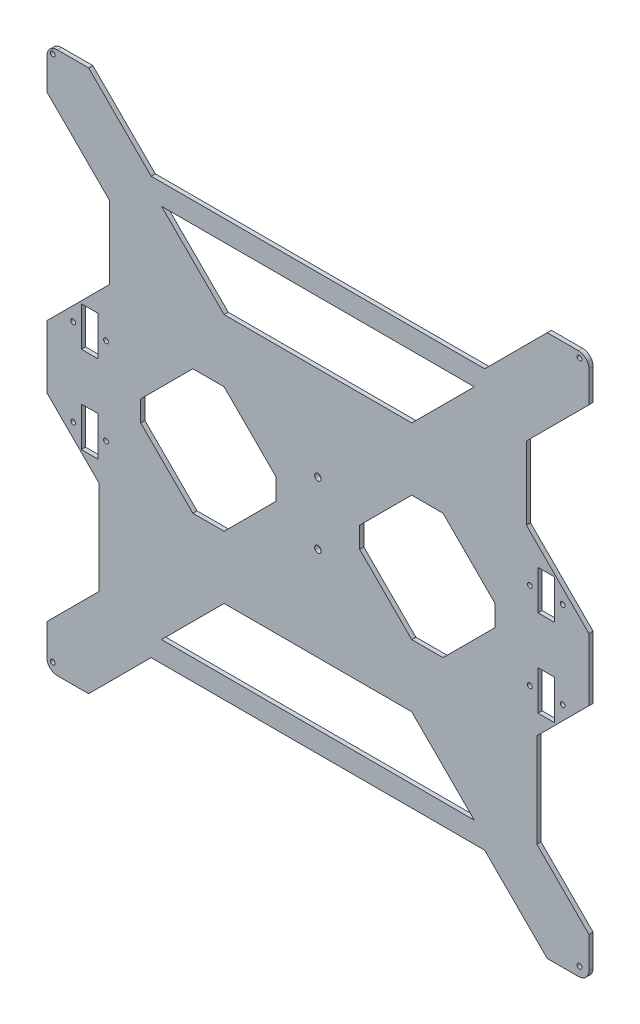
SolidWorks part; units mm, degrees
ref_plane "Front Plane" through (0, 0, 0) normal (0, 0, 1) x (1, 0, 0)
ref_plane "Top Plane" through (0, 0, 0) normal (0, 1, 0) x (1, 0, 0)
ref_plane "Right Plane" through (0, 0, 0) normal (1, 0, 0) x (0, 0, -1)
sketch "Model" plane through (0, 0, 0) normal (0, 0, 1) x (1, 0, 0)
  line L0 (38.5361, 132.6139) -> (38.5361, 132.4727)
  line L1 (38.5361, -178.6774) -> (38.5361, -178.7219)
  line L2 (-253.5639, -197.5861) -> (-253.5639, -197.7273)
  line L3 (-252.5813, 70.3317) -> (-252.5813, 25.8817)
  line L4 (-258.9313, -82.0683) -> (-258.9313, -139.2183)
  line L5 (38.5361, 132.6139) -> (38.5361, 132.4727)
  line L6 (38.5361, -178.6774) -> (38.5361, -178.7219)
  line L7 (7.7687, -139.2183) -> (7.7687, -82.0683)
  line L8 (1.4187, 25.8817) -> (1.4187, 70.3317)
  line L9 (-23.9813, 95.7317) -> (-227.1813, 95.7317)
  line L10 (-290.6813, 108.4317) -> (-252.5813, 70.3317)
  line L11 (-30.3313, -145.5683) -> (-68.4313, -107.4683)
  line L12 (-23.9813, -158.2683) -> (14.1187, -196.3683)
  line L13 (39.5187, 108.4317) -> (39.5187, 127.4817)
  line L14 (-227.1813, 95.7317) -> (-265.2813, 133.8317)
  line L15 (-220.8313, 83.0317) -> (-182.7313, 44.9317)
  line L16 (-274.6813, -57.7288) -> (-254.6813, -57.7288) construction
  line L17 (39.5187, -170.9683) -> (7.7687, -139.2183)
  line L18 (-265.2813, -196.3683) -> (-227.1813, -158.2683)
  line L19 (-182.7313, -107.4683) -> (-68.4313, -107.4683)
  line L20 (-264.6813, -57.7288) -> (-264.6813, -43.5832) construction
  line L21 (1.4187, 70.3317) -> (39.5187, 108.4317)
  line L22 (-23.9813, 95.7317) -> (14.1187, 133.8317)
  line L23 (-30.3313, 83.0317) -> (-68.4313, 44.9317)
  line L25 (-258.9313, -139.2183) -> (-290.6813, -170.9683)
  line L26 (-182.7313, 44.9317) -> (-68.4313, 44.9317)
  line L27 (-220.8313, -145.5683) -> (-182.7313, -107.4683)
  line L28 (-220.8313, -145.5683) -> (-30.3313, -145.5683)
  line L29 (-258.9313, -82.0683) -> (-290.6813, -50.3183)
  line L30 (-290.6813, -12.2183) -> (-290.6813, -50.3183)
  line L31 (-274.6813, -56.2683) -> (-274.6813, -31.2683) construction
  line L32 (-290.6813, -12.2183) -> (-252.5813, 25.8817)
  line L33 (-201.7813, -69.3683) -> (-233.5313, -37.6183)
  line L34 (-182.7313, -69.3683) -> (-201.7813, -69.3683)
  line L35 (1.4187, 25.8817) -> (39.5187, -12.2183)
  line L36 (39.5187, -12.2183) -> (39.5187, -50.3183)
  line L37 (-150.9813, -37.6183) -> (-182.7313, -69.3683)
  line L38 (39.5187, -50.3183) -> (22.4579, -67.3791)
  line L39 (22.4579, -67.3791) -> (7.7687, -82.0683)
  line L40 (-100.1813, -37.6183) -> (-100.1813, -24.9183)
  line L41 (-150.9813, -37.6183) -> (-150.9813, -24.9183)
  line L42 (-150.9813, -24.9183) -> (-182.7313, 6.8317)
  line L43 (-182.7313, 6.8317) -> (-201.7813, 6.8317)
  line L44 (-201.7813, 6.8317) -> (-233.5313, -24.9183)
  line L45 (-233.5313, -24.9183) -> (-233.5313, -37.6183)
  line L46 (-17.6313, -24.9183) -> (-17.6313, -37.6183)
  line L47 (-49.3813, 6.8317) -> (-17.6313, -24.9183)
  line L48 (-220.8313, 83.0317) -> (-30.3313, 83.0317)
  line L49 (-68.4313, 6.8317) -> (-49.3813, 6.8317)
  line L50 (-100.1813, -24.9183) -> (-68.4313, 6.8317)
  line L51 (-100.1813, -37.6183) -> (-68.4313, -69.3683)
  line L52 (-68.4313, -69.3683) -> (-49.3813, -69.3683)
  line L53 (-49.3813, -69.3683) -> (-17.6313, -37.6183)
  line L58 (-265.2813, -196.3683) -> (-284.3313, -196.3683)
  line L59 (-290.6813, -190.0183) -> (-290.6813, -170.9683)
  line L60 (-290.6813, 108.4317) -> (-290.6813, 127.4817)
  line L61 (-284.3313, 133.8317) -> (-265.2813, 133.8317)
  line L62 (14.1187, 133.8317) -> (33.1687, 133.8317)
  line L64 (39.5187, -170.9683) -> (39.5187, -190.0183)
  line L65 (33.1687, -196.3683) -> (14.1187, -196.3683)
  line L71 (-227.1813, -158.2683) -> (-23.9813, -158.2683)
  line L72 (38.5361, -178.6774) -> (38.5361, -178.7219)
  line L74 (-227.1813, -158.2683) -> (-23.9813, -158.2683)
  line L75 (38.5361, -178.6774) -> (38.5361, -178.7219)
  line L77 (-125.5813, 95.7317) -> (-125.5813, -158.2683) construction
  line L78 (-290.6813, -31.2683) -> (39.5187, -31.2683) construction
  arc A0 (33.1687, -196.3683) -> (39.5187, -190.0183) centre (33.1687, -190.0183) ccw
  arc A1 (-290.6813, -190.0183) -> (-284.3313, -196.3683) centre (-284.3313, -190.0183) ccw
  arc A2 (-290.6813, 127.4817) -> (-284.3313, 133.8317) centre (-284.3313, 127.4817) cw
  arc A3 (33.1687, 133.8317) -> (39.5187, 127.4817) centre (33.1687, 127.4817) cw
  circle A4 centre (-287.1253, -190.6025) radius 1.4605
  circle A5 centre (33.7529, -190.6025) radius 1.4605
  circle A6 centre (33.7529, 130.2757) radius 1.4605
  circle A7 centre (-287.1253, 130.2757) radius 1.4605
  circle A8 centre (-274.6813, -57.7288) radius 1.4605
  circle A9 centre (-254.6813, -57.7288) radius 1.4605
  circle A10 centre (23.5187, -57.7288) radius 1.4605
  circle A11 centre (3.5187, -57.7288) radius 1.4605
  circle A12 centre (23.5187, -4.8078) radius 1.4605
  circle A13 centre (3.5187, -4.8078) radius 1.4605
  circle A14 centre (-254.6813, -4.8078) radius 1.4605
  circle A15 centre (-274.6813, -4.8078) radius 1.4605
  circle A16 centre (-125.5813, -12.2183) radius 2
  circle A17 centre (-125.5813, -50.3183) radius 2
  point P72 (-125.5813, -31.2683)
  point P79 (-290.6813, -31.2683)
  point P114 (-125.5813, 83.0317)
  point P116 (39.5187, -31.2683)
  point P120 (-233.5313, -31.2683)
  point P129 (-150.9813, -31.2683)
  point P141 (-290.6813, -180.4933)
  point P149 (-125.5813, 44.9317)
  point P156 (-17.6313, -31.2683)
  dimension "D28" = 6.35
  dimension "D29" = 6.35
  dimension "D30" = 6.35
  dimension "D31" = 6.35
  dimension "D35" = 2.921
  dimension "D36" = 2.921
  dimension "D37" = 2.921
  dimension "D38" = 2.921
  dimension "D53" = 2.921
  dimension "D54" = 2.921
  dimension "D56" = 4
  dimension "D57" = 4
  dimension "D1" = 330.2
  dimension "D2" = 330.2
  dimension "D3" = 135
  dimension "D4" = 135
  dimension "D5" = 38.1
  dimension "D6" = 135
  dimension "D7" = 135
  dimension "D8" = 19.05
  dimension "D9" = 135
  dimension "D10" = 19.05
  dimension "D11" = 31.75
  dimension "D12" = 190.5
  dimension "D13" = 114.3
  dimension "D14" = 38.1
  dimension "D15" = 114.3
  dimension "D16" = 135
  dimension "D17" = 6.35
  dimension "D18" = 38.1
  dimension "D19" = 135
  dimension "D20" = 135
  dimension "D21" = 6.35
  dimension "D22" = 19.05
  dimension "D23" = 25.4
  dimension "D24" = 38.1
  dimension "D25" = 135
  dimension "D26" = 135
  dimension "D27" = 127
  dimension "D32" = 19.05
  dimension "D33" = 19.05
  dimension "D34" = 19.05
  dimension "D39" = 38.1
  dimension "D40" = 19.05
  dimension "D41" = 38.1
  dimension "D42" = 38.1
  dimension "D43" = 135
  dimension "D44" = 19.05
  dimension "D45" = 31.75
  dimension "D46" = 135
  dimension "D47" = 320.8782
  dimension "D48" = 320.8782
  dimension "D49" = 3.556
  dimension "D50" = 3.556
  dimension "D51" = 20
  dimension "D52" = 26
  dimension "D55" = 25
  dimension "D58" = 38.1
  dimension "D59" = 19.05
extrude "Boss-Extrude1" add sketch "Model" along normal mid plane 2.54
sketch "Sketch1" plane through (0, 0, 1.27) normal (0, 0, 1) x (1, 0, 0)
  line L1 (-269.6813, -45.7288) -> (-259.6813, -45.7288)
  line L2 (-269.6813, -45.7288) -> (-269.6813, -69.7288)
  line L3 (-269.6813, -69.7288) -> (-259.6813, -69.7288)
  line L4 (-259.6813, -45.7288) -> (-259.6813, -69.7288)
  line L5 (-269.6813, 7.1922) -> (-259.6813, 7.1922)
  line L6 (-269.6813, 7.1922) -> (-269.6813, -16.8078)
  line L7 (-269.6813, -16.8078) -> (-259.6813, -16.8078)
  line L8 (-259.6813, 7.1922) -> (-259.6813, -16.8078)
  line L9 (8.5187, 7.1922) -> (18.5187, 7.1922)
  line L10 (8.5187, 7.1922) -> (8.5187, -16.8078)
  line L11 (8.5187, -16.8078) -> (18.5187, -16.8078)
  line L12 (18.5187, 7.1922) -> (18.5187, -16.8078)
  line L13 (8.5187, -45.7288) -> (18.5187, -45.7288)
  line L14 (8.5187, -45.7288) -> (8.5187, -69.7288)
  line L15 (8.5187, -69.7288) -> (18.5187, -69.7288)
  line L16 (18.5187, -45.7288) -> (18.5187, -69.7288)
  circle A1 centre (-274.6813, -57.7288) radius 1.4605 construction
  circle A5 centre (-274.6813, -4.8078) radius 1.4605 construction
  circle A7 centre (-254.6813, -4.8078) radius 1.4605 construction
  circle A8 centre (23.5187, -4.8078) radius 1.4605 construction
  circle A9 centre (23.5187, -57.7288) radius 1.4605 construction
  dimension "D3" = 12
  dimension "D4" = 5
  dimension "D5" = 10
  dimension "D8" = 12
  dimension "D11" = 12
  dimension "D15" = 12
  dimension "D1" = 10
  dimension "D2" = 24
  dimension "D6" = 24
  dimension "D7" = 5
  dimension "D9" = 24
  dimension "D10" = 5
  dimension "D12" = 10
  dimension "D13" = 10
  dimension "D14" = 24
  dimension "D16" = 5
extrude "Cut-Extrude1" cut sketch "Sketch1" against normal blind 10
